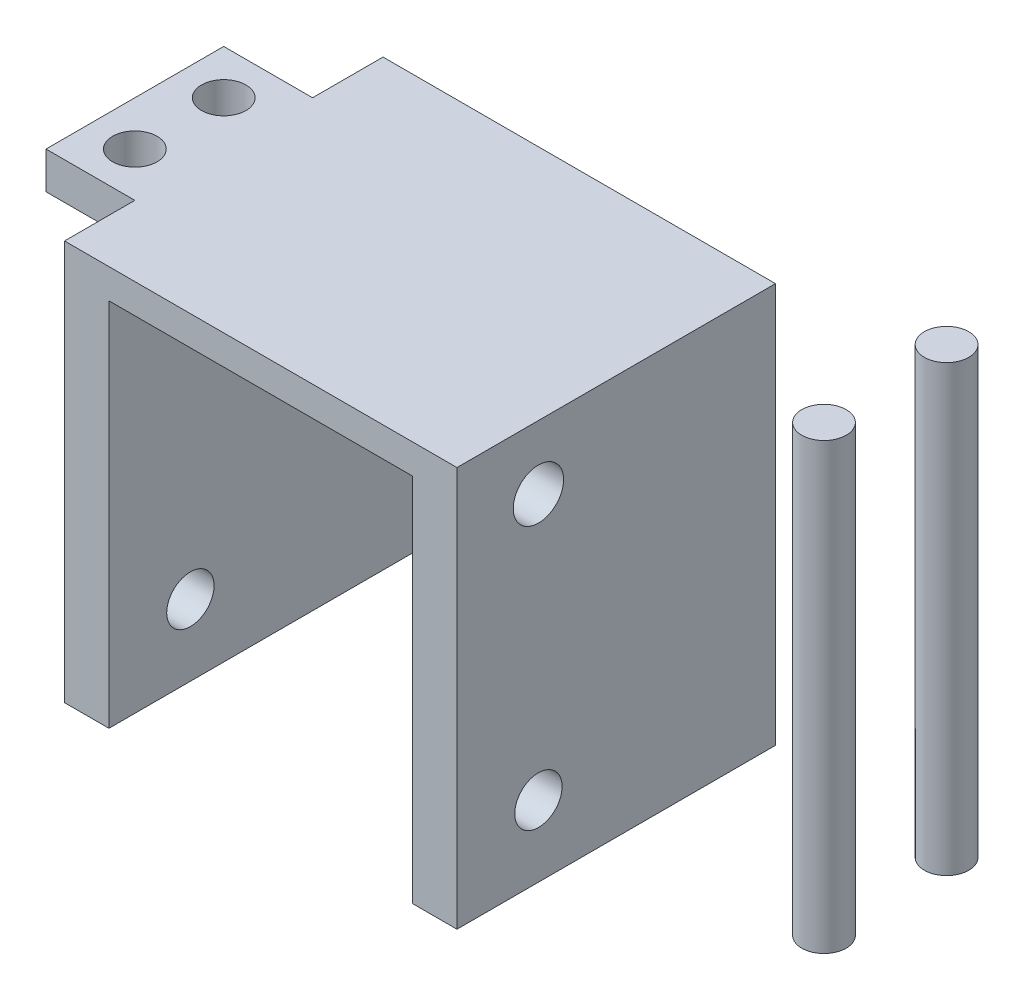
SolidWorks part; units mm, degrees
ref_plane "Front Plane" through (0, 0, 0) normal (0, 0, 1) x (1, 0, 0)
ref_plane "Top Plane" through (0, 0, 0) normal (0, 1, 0) x (1, 0, 0)
ref_plane "Right Plane" through (0, 0, 0) normal (1, 0, 0) x (0, 0, -1)
sketch "Sketch1" plane through (0, 0, 0) normal (0, 0, 1) x (1, 0, 0)
  line L1 (-2.1777, -34.964) -> (-28.6777, -34.964)
  line L2 (-2.1777, -34.964) -> (-2.1777, -7.964)
  line L3 (-2.1777, -7.964) -> (-28.6777, -7.964)
  line L4 (-28.6777, -34.964) -> (-28.6777, -7.964)
  line L5 (-2.1777, -34.964) -> (-28.6777, -7.964) construction
  line L6 (-2.1777, -7.964) -> (-28.6777, -34.964) construction
  point P0 (-15.4277, -21.464)
extrude "Boss-Extrude1" add sketch "Sketch1" along normal blind 36.7
sketch "Sketch2" plane through (0, 0, 0) normal (0, 0, -1) x (-1, 0, 0)
  line L0 (28.6777, -34.964) -> (2.1777, -34.964) construction
  line L1 (25.6777, -34.964) -> (5.1777, -34.964)
  line L2 (25.6777, -34.964) -> (25.6777, -9.964)
  line L3 (25.6777, -9.964) -> (5.1777, -9.964)
  line L4 (5.1777, -34.964) -> (5.1777, -9.964)
  line L5 (25.6777, -34.964) -> (5.1777, -9.964) construction
  line L6 (25.6777, -9.964) -> (5.1777, -34.964) construction
  line L9 (2.1777, -7.964) -> (28.6777, -7.964) construction
  line L10 (2.1777, -34.964) -> (2.1777, -7.964) construction
  line L11 (28.6777, -7.964) -> (28.6777, -34.964) construction
  point P0 (15.4277, -22.464)
  dimension "D1" = 0
  dimension "D2" = 3
  dimension "D3" = 3
  dimension "D4" = 2
extrude "Cut-Extrude1" cut sketch "Sketch2" against normal blind 36.7
sketch "Sketch3" plane through (-2.1777, 0, 0) normal (1, 0, 0) x (0, 0, -1)
  line L1 (-36.7, -34.964) -> (-36.7, -7.964) construction
  line L2 (-36.7, -9.964) -> (0, -9.964) construction
  circle A0 centre (-31.2, -12.264) radius 1.7
  circle A1 centre (-31.2, -30.164) radius 1.6
  dimension "D3" = 17.9
  dimension "D1" = 2.3
  dimension "D2" = 5.5
  dimension "D4" = 5.5
extrude "Cut-Extrude2" cut sketch "Sketch3" against normal blind 36.7
sketch "Sketch4" plane through (-2.1777, 0, 0) normal (1, 0, 0) x (0, 0, -1)
  line L1 (0, -34.964) -> (0, -7.964) construction
  line L2 (-36.7, -9.964) -> (0, -9.964) construction
  circle A0 centre (-12.0251, -21.164) radius 3
  dimension "D1" = 11.2
  dimension "D2" = 12.0251
extrude "Cut-Extrude3" cut sketch "Sketch4" against normal blind 36.7
sketch "Sketch8" plane through (0, -7.964, 0) normal (0, 1, 0) x (1, 0, 0)
  circle A0 centre (7.1574, -12.974) radius 1.5
  circle A1 centre (7.5744, -21.6698) radius 1.5
extrude "Boss-Extrude3" add sketch "Sketch8" against normal blind 30 separate body
sketch "Sketch9" plane through (0, 0, 0) normal (0, 0, -1) x (-1, 0, 0)
  line L1 (6.6484, -24.164) -> (0.7297, -24.164)
  line L2 (6.6484, -24.164) -> (6.6484, -18.164)
  line L3 (6.6484, -18.164) -> (0.7297, -18.164)
  line L4 (0.7297, -24.164) -> (0.7297, -18.164)
  line L5 (6.6484, -24.164) -> (0.7297, -18.164) construction
  line L6 (6.6484, -18.164) -> (0.7297, -24.164) construction
  line L7 (31.4578, -24.164) -> (24.7499, -24.164)
  line L8 (31.4578, -24.164) -> (31.4578, -18.164)
  line L9 (31.4578, -18.164) -> (24.7499, -18.164)
  line L10 (24.7499, -24.164) -> (24.7499, -18.164)
  line L11 (31.4578, -24.164) -> (24.7499, -18.164) construction
  line L12 (31.4578, -18.164) -> (24.7499, -24.164) construction
  line L13 (25.6777, -9.964) -> (5.1777, -9.964) construction
  point P0 (3.689, -21.164)
  point P5 (28.1039, -21.164)
  dimension "D1" = 14.2
  dimension "D2" = 14.2
extrude "Cut-Extrude4" cut sketch "Sketch9" against normal blind 12
sketch "Sketch11" plane through (-28.6777, 0, 0) normal (-1, 0, 0) x (0, 0, 1)
  line L0 (0, -7.964) -> (0, -18.164) construction
  line L1 (15.1914, -34.964) -> (0, -34.964)
  line L2 (15.1914, -34.964) -> (15.1914, 2.1035)
  line L3 (15.1914, 2.1035) -> (0, 2.1035)
  line L4 (0, -34.964) -> (0, 2.1035)
  line L5 (15.1914, -34.964) -> (0, 2.1035) construction
  line L6 (15.1914, 2.1035) -> (0, -34.964) construction
  line L7 (36.7, -34.964) -> (0, -34.964) construction
  point P0 (7.5957, -16.4302)
  dimension "D1" = 0
  dimension "D2" = 0
extrude "Cut-Extrude6" cut sketch "Sketch11" against normal blind 32
sketch "Sketch12" plane through (-28.6777, 0, 0) normal (-1, 0, 0) x (0, 0, 1)
  line L0 (36.7, -7.964) -> (15.1914, -7.964) construction
  line L1 (19.95, -7.964) -> (31.95, -7.964)
  line L2 (19.95, -7.964) -> (19.95, -10.464)
  line L3 (19.95, -10.464) -> (31.95, -10.464)
  line L4 (31.95, -7.964) -> (31.95, -10.464)
  line L5 (19.95, -7.964) -> (31.95, -10.464) construction
  line L6 (19.95, -10.464) -> (31.95, -7.964) construction
  line L7 (36.7, -7.964) -> (36.7, -34.964) construction
  point P0 (25.95, -9.214)
  dimension "D1" = 0
  dimension "D2" = 4.75
extrude "Boss-Extrude4" add sketch "Sketch12" along normal blind 6
sketch "Sketch13" plane through (0, -7.964, 0) normal (0, 1, 0) x (1, 0, 0)
  line L0 (-34.6777, -19.95) -> (-28.6777, -19.95) construction
  line L1 (-34.6777, -31.95) -> (-28.6777, -31.95) construction
  line L2 (-34.6777, -31.95) -> (-34.6777, -19.95) construction
  circle A0 centre (-31.6777, -22.95) radius 1.5
  circle A1 centre (-31.6777, -28.95) radius 1.5
  dimension "D1" = 3
  dimension "D2" = 3
  dimension "D3" = 3
  dimension "D4" = 3
extrude "Cut-Extrude7" cut sketch "Sketch13" against normal blind 6
move or copy body "Body-Move/Copy4" bodies to move or copy 115 copy yes number of copies 1 translate (-70.8216, 0, 0) parameters "D1"=70.8216, "D2"=0, "D3"=0
move or copy body "Body-Move/Copy5" bodies to move or copy 108 copy yes number of copies 1 translate (-69.7545, 0, 0) parameters "D1"=69.7545, "D2"=0, "D3"=0
move or copy body "Body-Move/Copy6" bodies to move or copy 109 copy yes number of copies 1 translate (-71.5211, 0, 0) parameters "D1"=71.5211, "D2"=0, "D3"=0
sketch "Sketch14" plane through (0, -7.964, 0) normal (0, 1, 0) x (1, 0, 0)
  line L0 (-99.4994, -19.95) -> (-99.4994, -15.1914) construction
  line L1 (-111.2318, -2.8793) -> (-99.4994, -2.8793)
  line L2 (-111.2318, -2.8793) -> (-111.2318, -34.8559)
  line L3 (-111.2318, -34.8559) -> (-99.4994, -34.8559)
  line L4 (-99.4994, -2.8793) -> (-99.4994, -34.8559)
  line L5 (-111.2318, -2.8793) -> (-99.4994, -34.8559) construction
  line L6 (-111.2318, -34.8559) -> (-99.4994, -2.8793) construction
  point P0 (-105.3656, -18.8676)
  dimension "D1" = 0
extrude "Cut-Extrude8" cut sketch "Sketch14" against normal blind 10
sketch "Sketch15" plane through (0, -7.964, 0) normal (0, 1, 0) x (1, 0, 0)
  line L0 (-72.9994, -36.7) -> (-72.9994, -15.1914) construction
  line L1 (-72.9994, -19.9414) -> (-66.9994, -19.9414)
  line L2 (-72.9994, -19.9414) -> (-72.9994, -31.95)
  line L3 (-72.9994, -31.95) -> (-66.9994, -31.95)
  line L4 (-66.9994, -19.9414) -> (-66.9994, -31.95)
  line L5 (-72.9994, -19.9414) -> (-66.9994, -31.95) construction
  line L6 (-72.9994, -31.95) -> (-66.9994, -19.9414) construction
  line L7 (-72.9994, -36.7) -> (-99.4994, -36.7) construction
  line L8 (-72.9994, -15.1914) -> (-99.4994, -15.1914) construction
  circle A0 centre (-69.9994, -22.9414) radius 1.5
  circle A1 centre (-69.9994, -28.95) radius 1.5
  point P0 (-69.9994, -25.9457)
  dimension "D4" = 3
  dimension "D5" = 3
  dimension "D6" = 3
  dimension "D7" = 3
  dimension "D1" = 0
  dimension "D2" = 4.75
  dimension "D3" = 4.75
extrude "Boss-Extrude5" add sketch "Sketch15" against normal blind 2.5
sketch "Sketch17" plane through (0, -7.964, 0) normal (0, 1, 0) x (1, 0, 0)
  line L1 (-154.0847, 22.4918) -> (-54.9963, 22.4918)
  line L2 (-154.0847, 22.4918) -> (-154.0847, -43.3378)
  line L3 (-154.0847, -43.3378) -> (-54.9963, -43.3378)
  line L4 (-54.9963, 22.4918) -> (-54.9963, -43.3378)
  line L5 (-154.0847, 22.4918) -> (-54.9963, -43.3378) construction
  line L6 (-154.0847, -43.3378) -> (-54.9963, 22.4918) construction
  point P0 (-104.5405, -10.423)
extrude "Cut-Extrude9" cut sketch "Sketch17" against normal blind 50
